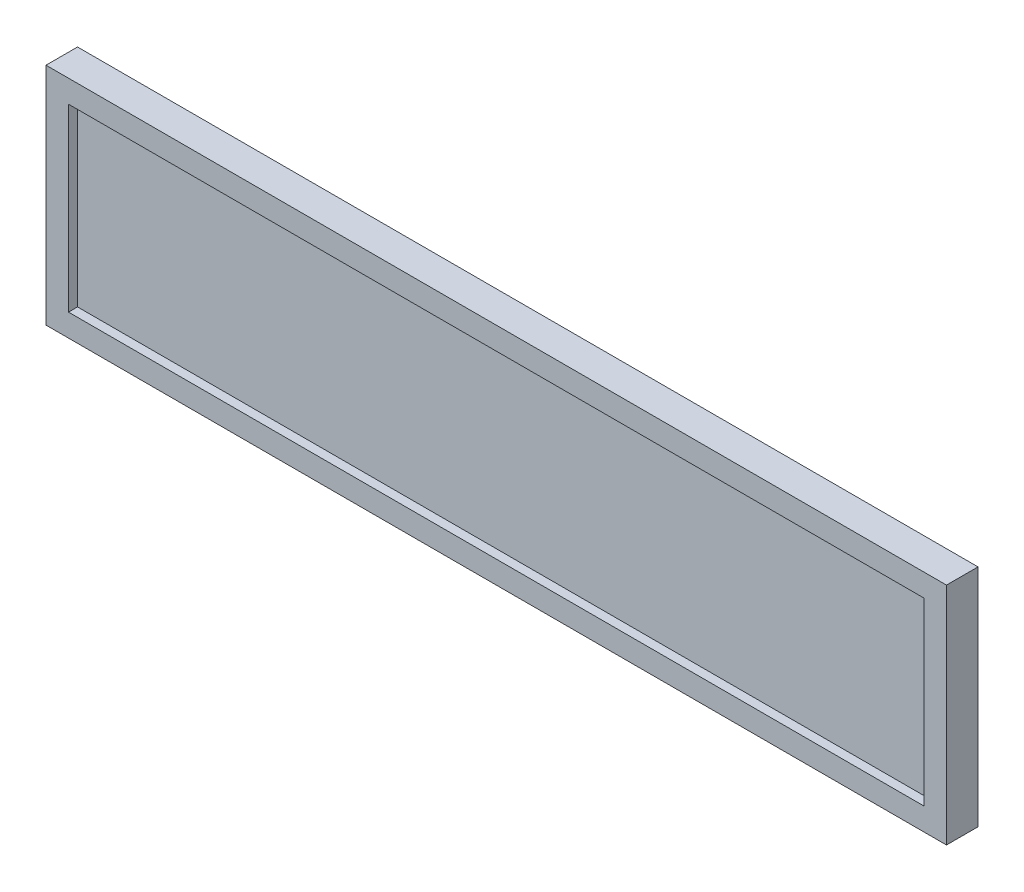
SolidWorks part; units mm, degrees
ref_plane "Front Plane" through (0, 0, 0) normal (0, 0, 1) x (1, 0, 0)
ref_plane "Top Plane" through (0, 0, 0) normal (0, 1, 0) x (1, 0, 0)
ref_plane "Right Plane" through (0, 0, 0) normal (1, 0, 0) x (0, 0, -1)
sketch "Esquisse1" plane through (0, 0, 0) normal (0, 0, 1) x (1, 0, 0)
  line L1 (-5000, 1250) -> (5000, 1250)
  line L2 (-5000, 1250) -> (-5000, -1250)
  line L3 (-5000, -1250) -> (5000, -1250)
  line L4 (5000, 1250) -> (5000, -1250)
  line L5 (-5000, 1250) -> (5000, -1250) construction
  line L6 (-5000, -1250) -> (5000, 1250) construction
  point P0 (0, 0)
  dimension "D1" = 10000
  dimension "D2" = 2500
extrude "Boss.-Extru.1" add sketch "Esquisse1" along normal blind 250
sketch "Esquisse2" plane through (0, 0, 250) normal (0, 0, 1) x (1, 0, 0)
  line L0 (4750, 1000) -> (-4750, 1000)
  line L1 (-4750, 1000) -> (-4750, -1000)
  line L2 (-4750, -1000) -> (4750, -1000)
  line L3 (4750, -1000) -> (4750, 1000)
  line L4 (5000, -1250) -> (5000, 1250)
  line L5 (5000, 1250) -> (-5000, 1250)
  line L6 (-5000, 1250) -> (-5000, -1250)
  line L7 (-5000, -1250) -> (5000, -1250)
  line L8 (5000, -1250) -> (5000, 1250)
  line L9 (5000, 1250) -> (-5000, 1250)
  line L10 (-5000, 1250) -> (-5000, -1250)
  line L11 (-5000, -1250) -> (5000, -1250)
  dimension "D1" = 0
  dimension "D2" = 250
extrude "Boss.-Extru.2" add sketch "Esquisse2" along normal blind 100
